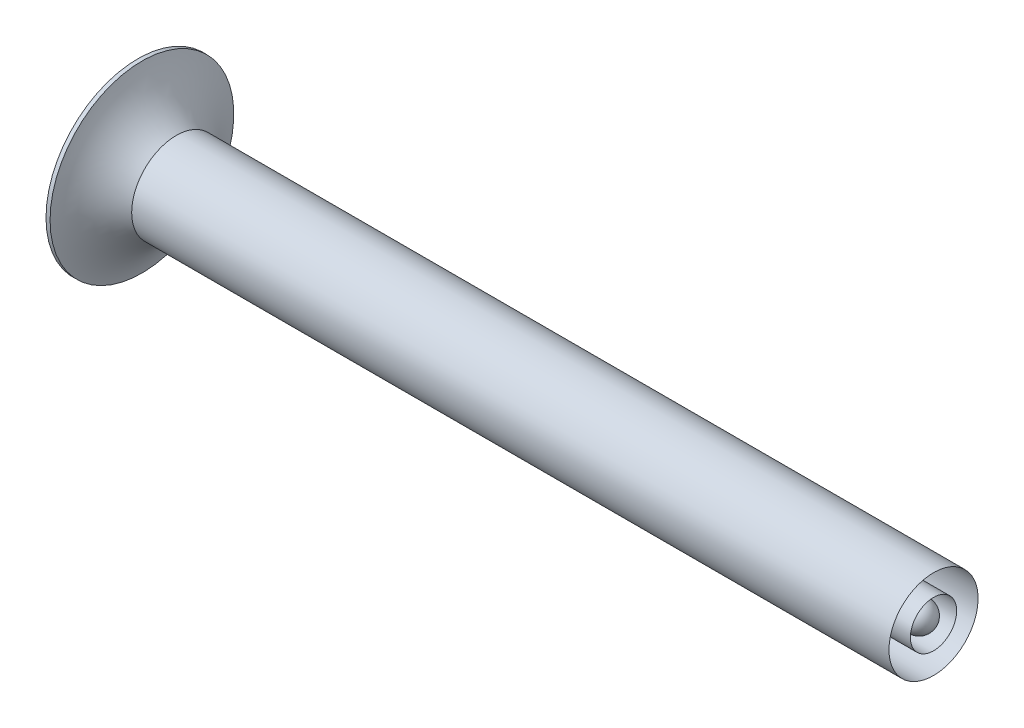
SolidWorks part; units mm, degrees
ref_plane "Front Plane" through (0, 0, 0) normal (0, 0, 1) x (1, 0, 0)
ref_plane "Top Plane" through (0, 0, 0) normal (0, 1, 0) x (1, 0, 0)
ref_plane "Right Plane" through (0, 0, 0) normal (1, 0, 0) x (0, 0, -1)
sketch "Sketch1" plane through (0, 0, 0) normal (0, 0, 1) x (1, 0, 0)
  line L0 (0, -4.0323) -> (0, 0)
  line L1 (0, 4.0322) -> (0.1778, 4.0322) construction
  line L2 (0.1778, 4.0322) -> (1.67, 2.54) construction
  line L3 (1.67, 2.54) -> (3.8608, 1.27) construction
  line L4 (3.8608, 1.27) -> (3.8608, -1.27) construction
  line L5 (3.8608, -1.27) -> (1.67, -2.54) construction
  line L6 (1.67, -2.54) -> (0.1778, -4.0323) construction
  line L7 (0.1778, -4.0323) -> (0, -4.0323)
  line L8 (0.1778, 4.0322) -> (0.1778, -4.0323) construction
  line L9 (1.67, 2.54) -> (1.67, -2.54) construction
  line L10 (0, 0) -> (34.29, 0) construction
  line L11 (3.8608, 1.27) -> (29.5083, 1.27) construction
  line L12 (3.8608, -1.27) -> (12.065, -1.27)
  line L13 (31.4376, -1.016) -> (34.3729, -0.6296)
  line L14 (34.3729, 0.6296) -> (29.5083, 1.27) construction
  line L15 (29.5083, 1.27) -> (29.5083, -1.27) construction
  line L16 (34.3729, -0.6296) -> (39.1549, 0) construction
  line L17 (39.1549, 0) -> (34.3729, 0.6296) construction
  line L18 (0, 0) -> (34.925, 0)
  line L19 (0, 0) -> (0, 4.0322) construction
  line L20 (12.065, -1.27) -> (13.9943, -1.016)
  line L22 (13.9943, -1.016) -> (31.4376, -1.016)
  line L23 (12.065, -1.27) -> (29.5083, -1.27) construction
  line L24 (29.5083, -1.27) -> (31.4376, -1.016) construction
  line L25 (13.9943, -1.016) -> (13.9943, 1.016) construction
  arc A0 (34.925, 0) -> (34.3729, -0.6296) centre (34.29, 0) cw
  arc A1 (34.3729, 0.6296) -> (34.925, 0) centre (34.29, 0) cw construction
  arc A2 (3.8608, -1.27) -> (0.1778, -4.0323) centre (3.8608, -5.1065) ccw
  point P3 (13.9943, 0)
  point P14 (3.8608, 0)
  point P26 (3.8608, -4.2849)
  dimension "D10" = 0.635
  dimension "D1" = 8.0645
  dimension "D2" = 3.683
  dimension "D3" = 45
  dimension "D4" = 45
  dimension "D5" = 5.08
  dimension "D6" = 2.54
  dimension "D7" = 3.8608
  dimension "D8" = 34.925
  dimension "D9" = 15
  dimension "D11" = 7.5
  dimension "D12" = 2.032
  dimension "D13" = 22.86
revolve "Revolve1" add sketch "Sketch1" angle 360 about L18
sketch "Sketch2" plane through (0, 0, 0) normal (1, 0, 0) x (0, 0, -1)
  circle A1 centre (0, 0) radius 1.016
  circle A2 centre (0, 0) radius 1.016 construction
surface "Max Pre-Drill Diameter" sketch "Sketch2"
sketch "Sketch3" plane through (0, 0, 0) normal (-1, 0, 0) x (0, 0, 1)
  circle A0 centre (0, 0) radius 1.9558
  dimension "D1" = 3.9116
surface "Thread Diameter" sketch "Sketch3"
